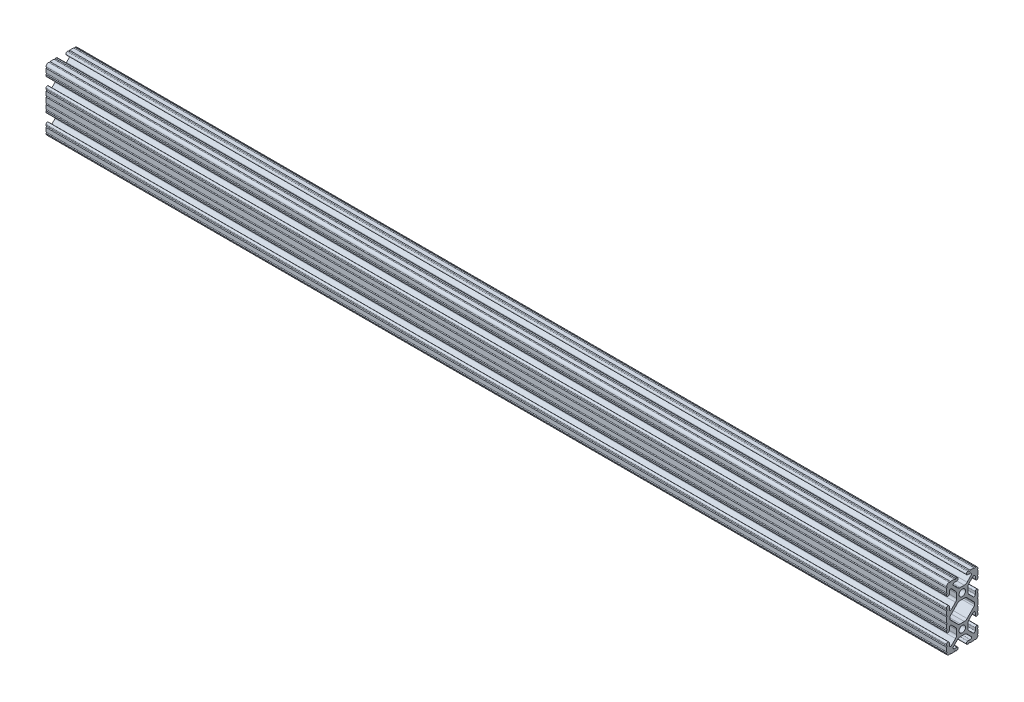
SolidWorks part; units mm, degrees
ref_plane "Front Plane" through (0, 0, 0) normal (0, 0, 1) x (1, 0, 0)
ref_plane "Top Plane" through (0, 0, 0) normal (0, 1, 0) x (1, 0, 0)
ref_plane "Right Plane" through (0, 0, 0) normal (1, 0, 0) x (0, 0, -1)
sketch "Sketch1" plane through (0, 0, 0) normal (1, 0, 0) x (0, 0, -1)
  line L44 (-4.3561, -23.1902) -> (-6.3702, -23.1902) construction
  line L45 (-7.1192, -21.3818) -> (-3.8845, -18.1471) construction
  line L46 (-1.6395, -17.2172) -> (1.6395, -17.2172) construction
  line L47 (3.8845, -18.1471) -> (7.1192, -21.3818) construction
  line L48 (6.3702, -23.1902) -> (4.3561, -23.1902) construction
  line L72 (-12.7, 0) -> (12.7, 0) construction
  line L73 (0, -25.4) -> (0, 25.4) construction
  line L74 (-10.5918, 25.4) -> (10.5918, 25.4) construction
  line L76 (-3.2512, -24.2951) -> (3.2512, -24.2951) construction
  line L79 (12.7, 23.2918) -> (12.7, -23.2918) construction
  line L81 (4.3561, -25.4) -> (10.5918, -25.4) construction
  line L82 (-10.5918, -25.4) -> (-4.3561, -25.4) construction
  line L84 (-12.7, 23.2918) -> (-12.7, -23.2918) construction
  arc A11 (12.7, 23.2918) -> (10.5918, 25.4) centre (10.5918, 23.2918) ccw construction
  arc A22 (-10.5918, 25.4) -> (-12.7, 23.2918) centre (-10.5918, 23.2918) ccw construction
  arc A43 (-12.7, -23.2918) -> (-10.5918, -25.4) centre (-10.5918, -23.2918) ccw construction
  arc A46 (-4.3561, -25.4) -> (-4.3561, -23.1902) centre (-4.3561, -24.2951) ccw construction
  arc A47 (-7.1192, -21.3818) -> (-6.3702, -23.1902) centre (-6.3702, -22.1309) ccw construction
  arc A48 (-1.6395, -17.2172) -> (-3.8845, -18.1471) centre (-1.6395, -20.3922) ccw construction
  arc A49 (3.8845, -18.1471) -> (1.6395, -17.2172) centre (1.6395, -20.3922) ccw construction
  arc A50 (6.3702, -23.1902) -> (7.1192, -21.3818) centre (6.3702, -22.1309) ccw construction
  arc A51 (4.3561, -23.1902) -> (4.3561, -25.4) centre (4.3561, -24.2951) ccw construction
  arc A54 (10.5918, -25.4) -> (12.7, -23.2918) centre (10.5918, -23.2918) ccw construction
  dimension "Corner Radius" = 2.1082
  dimension "Slot Bottom Radius" = 3.175
  dimension "Slot Width Radius" = 1.0593
  dimension "T Slot Depth" = 5.973
  dimension "T Slot Width" = 6.5024
  dimension "Rail Width" = 25.4
  dimension "Rail Height" = 50.8
  dimension "D4" = 45
  dimension "Slot Max Width" = 14.859
  dimension "Leg Thickness" = 2.2098
sketch "Sketch7" plane through (0, 0, 0) normal (1, 0, 0) x (0, 0, -1)
  line L0 (0, -25.4) -> (0, 25.4) construction
  line L1 (-10.5918, -25.4) -> (-4.3561, -25.4) construction
  line L2 (-12.7, 23.2918) -> (-12.7, -23.2918) construction
  line L4 (0, -8.1828) -> (0, -17.2172) construction
  line L5 (-1.6395, -17.2172) -> (1.6395, -17.2172) construction
  line L6 (4.3561, -25.4) -> (10.5918, -25.4) construction
  line L10 (-3.8845, 7.2529) -> (-9.5718, 1.5657) construction
  line L11 (-10.033, 0.4521) -> (-10.033, -0.4521) construction
  line L12 (-9.5718, -1.5657) -> (-3.8845, -7.2529) construction
  line L13 (-1.6395, -8.1828) -> (1.6395, -8.1828) construction
  line L14 (3.8845, -7.2529) -> (9.5718, -1.5657) construction
  line L15 (10.033, -0.4521) -> (10.033, 0.4521) construction
  line L16 (9.5718, 1.5657) -> (3.8845, 7.2529) construction
  line L17 (1.6395, 8.1828) -> (-1.6395, 8.1828) construction
  line L23 (-12.7, 0) -> (12.7, 0) construction
  circle A0 centre (0, 12.7) radius 2.6035 construction
  circle A1 centre (0, -12.7) radius 2.6035 construction
  arc A2 (3.8845, -18.1471) -> (1.6395, -17.2172) centre (1.6395, -20.3922) ccw construction
  circle A3 centre (-5.8166, -25.4) radius 0.508 construction
  arc A10 (-9.5718, 1.5657) -> (-10.033, 0.4521) centre (-8.4582, 0.4521) ccw construction
  arc A11 (-10.033, -0.4521) -> (-9.5718, -1.5657) centre (-8.4582, -0.4521) ccw construction
  arc A12 (-3.8845, -7.2529) -> (-1.6395, -8.1828) centre (-1.6395, -5.0078) ccw construction
  arc A13 (1.6395, -8.1828) -> (3.8845, -7.2529) centre (1.6395, -5.0078) ccw construction
  arc A14 (9.5718, -1.5657) -> (10.033, -0.4521) centre (8.4582, -0.4521) ccw construction
  arc A15 (10.033, 0.4521) -> (9.5718, 1.5657) centre (8.4582, 0.4521) ccw construction
  arc A16 (3.8845, 7.2529) -> (1.6395, 8.1828) centre (1.6395, 5.0078) ccw construction
  arc A17 (-1.6395, 8.1828) -> (-3.8845, 7.2529) centre (-1.6395, 5.0078) ccw construction
  point P40 (-10.0584, -25.4)
  point P41 (-5.8166, -25.4)
  point P42 (5.8166, -25.4)
  point P43 (10.0584, -25.4)
  point P44 (0, 8.1828)
  point P46 (-10.033, 0)
  dimension "Center Hole Diameter" = 5.207
  dimension "Center Radius" = 1.5748
  dimension "Grip Hole Diameter" = 1.016
  dimension "Center Hole Spacing" = 25.4
  dimension "Center Thickness" = 2.667
  dimension "D4" = 45
  dimension "Grip Spacing" = 4.2418
  dimension "D1" = 12.7
  dimension "Grip Center" = 5.8166
sketch "Sketch2" plane through (0, 0, 0) normal (0, 0, 1) x (1, 0, 0)
  line L0 (-363.5375, 0) -> (363.5375, 0) construction
  line L1 (-363.5375, 12.7) -> (363.5375, 12.7) construction
  line L2 (-363.5375, -12.7) -> (363.5375, -12.7) construction
  point P2 (-312.7375, 0)
  point P4 (312.7375, 0)
  dimension "Length" = 727.075
  dimension "D1" = 50.8
  dimension "D2" = 50.8
sketch "Sketch3" plane through (0, 0, 0) normal (1, 0, 0) x (0, 0, -1)
  line L210 (-10.5918, 25.4) -> (10.5918, 25.4)
  line L211 (-12.7, 23.2918) -> (-12.7, -23.2918)
  line L212 (-10.5918, -25.4) -> (10.5918, -25.4)
  line L213 (12.7, 23.2918) -> (12.7, -23.2918)
  arc A208 (-12.7, -23.2918) -> (-10.5918, -25.4) centre (-10.5918, -23.2918) ccw
  arc A209 (10.5918, -25.4) -> (12.7, -23.2918) centre (10.5918, -23.2918) ccw
  arc A210 (10.5918, 25.4) -> (12.7, 23.2918) centre (10.5918, 23.2918) cw
  arc A211 (-10.5918, 25.4) -> (-12.7, 23.2918) centre (-10.5918, 23.2918) ccw
extrude "Boss-Extrude1" add sketch "Sketch3" along normal up to vertex (363.5375 mm away) and the other way up to vertex (363.5375 mm away) up to point (363.5375, 0, 0) other way up to point (-363.5375, 0, 0)
sketch "Sketch8" plane through (0, 0, 0) normal (1, 0, 0) x (0, 0, -1)
  line L0 (-4.3561, -25.4) -> (-4.3561, -27.4141)
  line L1 (-4.3561, -27.4141) -> (4.3561, -27.4141)
  line L2 (4.3561, -27.4141) -> (4.3561, -25.4)
  line L3 (4.3561, -23.1902) -> (6.3702, -23.1902)
  line L4 (7.1192, -21.3818) -> (3.8845, -18.1471)
  line L5 (-1.6395, -17.2172) -> (1.6395, -17.2172)
  line L6 (-3.8845, -18.1471) -> (-7.1192, -21.3818)
  line L7 (-4.3561, -23.1902) -> (-6.3702, -23.1902)
  arc A0 (-3.8845, -18.1471) -> (-1.6395, -17.2172) centre (-1.6395, -20.3922) cw
  arc A1 (1.6395, -17.2172) -> (3.8845, -18.1471) centre (1.6395, -20.3922) cw
  arc A2 (-7.1192, -21.3818) -> (-6.3702, -23.1902) centre (-6.3702, -22.1309) ccw
  arc A3 (-4.3561, -23.1902) -> (-4.3561, -25.4) centre (-4.3561, -24.2951) cw
  arc A4 (4.3561, -25.4) -> (4.3561, -23.1902) centre (4.3561, -24.2951) cw
  arc A5 (6.3702, -23.1902) -> (7.1192, -21.3818) centre (6.3702, -22.1309) ccw
extrude "Cut-Extrude3" cut sketch "Sketch8" against normal through all both and the other way through all
sketch "Sketch9" plane through (0, 0, 0) normal (1, 0, 0) x (0, 0, -1)
  circle A0 centre (-10.0584, -25.4) radius 0.508
  circle A1 centre (-5.8166, -25.4) radius 0.508
  circle A2 centre (5.8166, -25.4) radius 0.508
  circle A3 centre (10.0584, -25.4) radius 0.508
  circle A4 centre (-5.8166, -25.4) radius 0.508 construction
extrude "Cut-Extrude4" cut sketch "Sketch9" against normal through all both and the other way through all
pattern_circular "CirPattern1" count 2 every 90 about axis through (0, -12.7, 0) along (1, 0, 0) of "Cut-Extrude3", "Cut-Extrude4"
mirror "Mirror1" about plane through (0, 0, 0) normal (0, 1, 0) of "CirPattern1", "Cut-Extrude3", "Cut-Extrude4"
sketch "Sketch4" plane through (0, 0, 0) normal (1, 0, 0) x (0, 0, -1)
  circle A0 centre (0, 12.7) radius 2.6035
  circle A1 centre (0, -12.7) radius 2.6035
  circle A3 centre (0, 12.7) radius 2.6035 construction
extrude "Cut-Extrude1" cut sketch "Sketch4" against normal through all both and the other way through all
sketch "Sketch5" plane through (0, 0, 0) normal (1, 0, 0) x (0, 0, -1)
  line L0 (-9.5718, 1.5657) -> (-3.8845, 7.2529)
  line L1 (-1.6395, 8.1828) -> (1.6395, 8.1828)
  line L2 (3.8845, 7.2529) -> (9.5718, 1.5657)
  line L3 (10.033, 0.4521) -> (10.033, -0.4521)
  line L4 (9.5718, -1.5657) -> (3.8845, -7.2529)
  line L5 (1.6395, -8.1828) -> (-1.6395, -8.1828)
  line L6 (-3.8845, -7.2529) -> (-9.5718, -1.5657)
  line L7 (-10.033, 0.4521) -> (-10.033, -0.4521)
  line L8 (3.8845, -7.2529) -> (9.5718, -1.5657) construction
  arc A0 (-10.033, 0.4521) -> (-9.5718, 1.5657) centre (-8.4582, 0.4521) cw
  arc A1 (-3.8845, 7.2529) -> (-1.6395, 8.1828) centre (-1.6395, 5.0078) cw
  arc A2 (1.6395, 8.1828) -> (3.8845, 7.2529) centre (1.6395, 5.0078) cw
  arc A3 (9.5718, 1.5657) -> (10.033, 0.4521) centre (8.4582, 0.4521) cw
  arc A4 (10.033, -0.4521) -> (9.5718, -1.5657) centre (8.4582, -0.4521) cw
  arc A5 (3.8845, -7.2529) -> (1.6395, -8.1828) centre (1.6395, -5.0078) cw
  arc A6 (-1.6395, -8.1828) -> (-3.8845, -7.2529) centre (-1.6395, -5.0078) cw
  arc A7 (-9.5718, -1.5657) -> (-10.033, -0.4521) centre (-8.4582, -0.4521) cw
extrude "Cut-Extrude2" cut sketch "Sketch5" against normal through all both and the other way through all
equation "\"D1@Sketch2\" = \"Rail Height@Sketch1\""
equation "\"D2@Sketch2\"=\"D1@Sketch2\""
equation "\"D1@Sketch7\" = \"Center Hole Spacing@Sketch7\" / 2"
